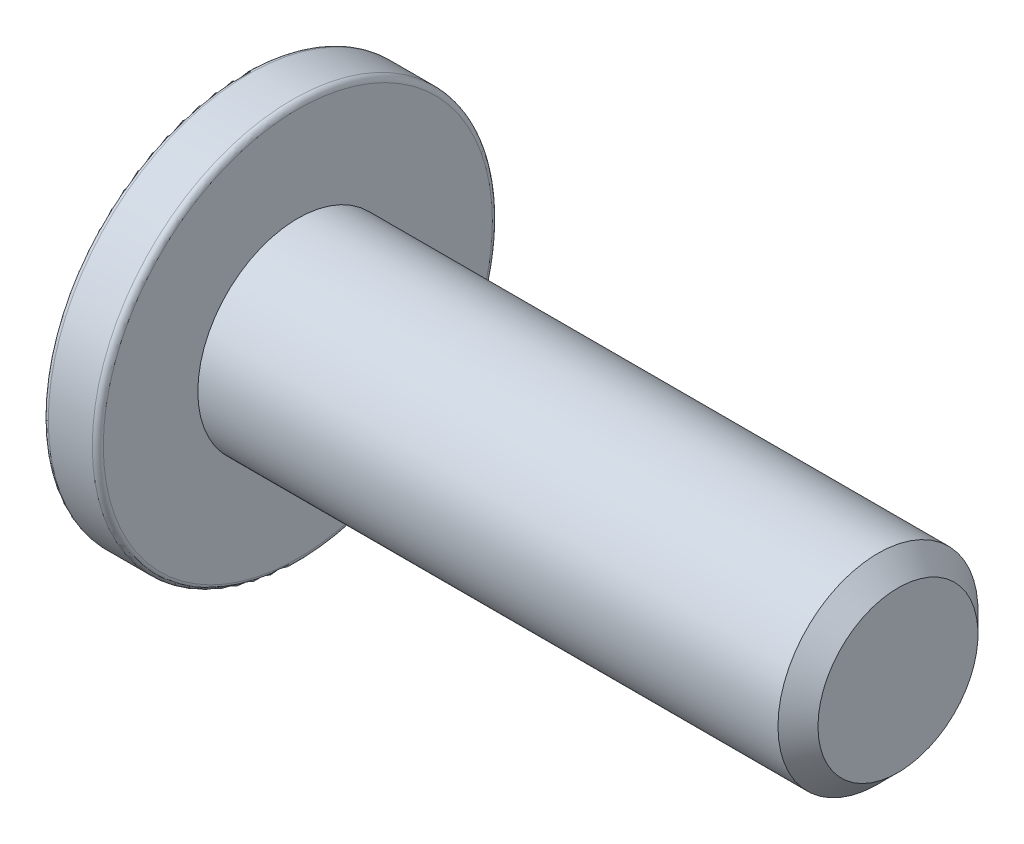
SolidWorks part; units mm, degrees
ref_plane "前视基准面" through (0, 0, 0) normal (0, 0, 1) x (1, 0, 0)
ref_plane "上视基准面" through (0, 0, 0) normal (0, 1, 0) x (1, 0, 0)
ref_plane "右视基准面" through (0, 0, 0) normal (1, 0, 0) x (0, 0, -1)
sketch "草图1" plane through (0, 0, 0) normal (0, 0, 1) x (1, 0, 0)
  line L0 (11.6, 2) -> (12, 1.6)
  line L1 (0, 0) -> (-1.1, 0)
  line L2 (0, 0) -> (0, 3.89)
  line L3 (-0.11, 4) -> (-0.99, 4)
  line L4 (-1.1, 0) -> (-1.1, 3.89)
  line L5 (0, 0) -> (12, 0)
  line L6 (0, 0) -> (0, 2)
  line L7 (0, 2) -> (11.6, 2)
  line L8 (12, 0) -> (12, 1.6)
  arc A0 (0, 3.89) -> (-0.11, 4) centre (-0.11, 3.89) ccw
  arc A1 (-0.99, 4) -> (-1.1, 3.89) centre (-0.99, 3.89) ccw
  dimension "D5" = 0.11
  dimension "D1" = 4
  dimension "D2" = 2
  dimension "D3" = 1.1
  dimension "D4" = 12
  dimension "D6" = 45
  dimension "D7" = 0.4
revolve "旋转1" add sketch "草图1" angle 360 about L5
cosmetic thread "装饰螺纹线1"
sketch "草图2" plane through (-1.1, 0, 0) normal (-1, 0, 0) x (0, 0, 1)
  line L1 (1.25, -0.7217) -> (1.25, 0.7217)
  line L2 (1.25, 0.7217) -> (0, 1.4434)
  line L3 (0, 1.4434) -> (-1.25, 0.7217)
  line L4 (-1.25, 0.7217) -> (-1.25, -0.7217)
  line L5 (-1.25, -0.7217) -> (0, -1.4434)
  line L6 (0, -1.4434) -> (1.25, -0.7217)
  circle A0 centre (0, 0) radius 1.25 construction
  dimension "D1" = 2.5
extrude "切除-拉伸1" cut sketch "草图2" against normal blind 0.55
equation "\"M\"=4"
equation "\"L\"=12"
equation "\"K\"=1.1"
equation "\"S\"=2.5"
equation "\"dk\"=8"
equation "\"D1@草图1\"=\"dk\"/2"
equation "\"D2@草图1\"=\"M\"/2"
equation "\"D3@草图1\"=\"K\""
equation "\"D4@草图1\"=\"L\""
equation "\"D5@草图1\"=\"K\"/10"
equation "\"D7@草图1\"=\"M\"/10"
equation "\"D1@草图2\"=\"S\""
equation "\"D1@切除-拉伸1\"=\"K\"/2"
equation "\"D2@装饰螺纹线1\"=\"M\"*0.86"
